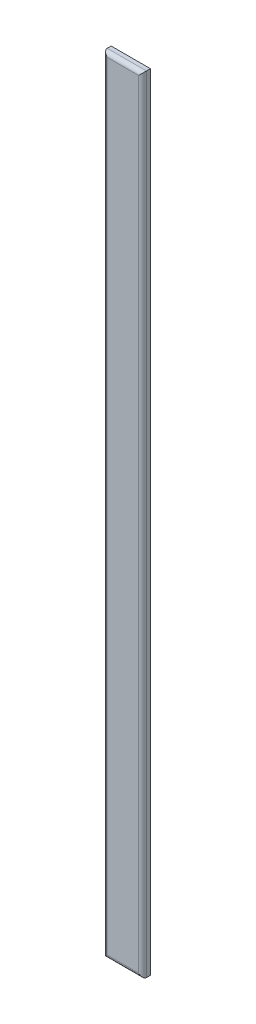
SolidWorks part; units mm, degrees
material "Rubber"
ref_plane "Front Plane" through (0, 0, 0) normal (0, 0, 1) x (1, 0, 0)
ref_plane "Top Plane" through (0, 0, 0) normal (0, 1, 0) x (1, 0, 0)
ref_plane "Right Plane" through (0, 0, 0) normal (1, 0, 0) x (0, 0, -1)
sketch "Sketch1" plane through (0, 0, 0) normal (0, 0, 1) x (1, 0, 0)
  line L0 (0, 0) -> (5, 0)
  line L1 (5, 0) -> (5, 100)
  line L2 (5, 100) -> (0, 100)
  line L3 (0, 100) -> (0, 0)
  dimension "D1" = 100
  dimension "D2" = 5
extrude "Boss-Extrude1" add sketch "Sketch1" along normal blind 1
fillet "Fillet1" radius 0.5 4 edges at (2.5, 100, 1) (5, 50, 1) (2.5, 0, 1) (0, 50, 1)
